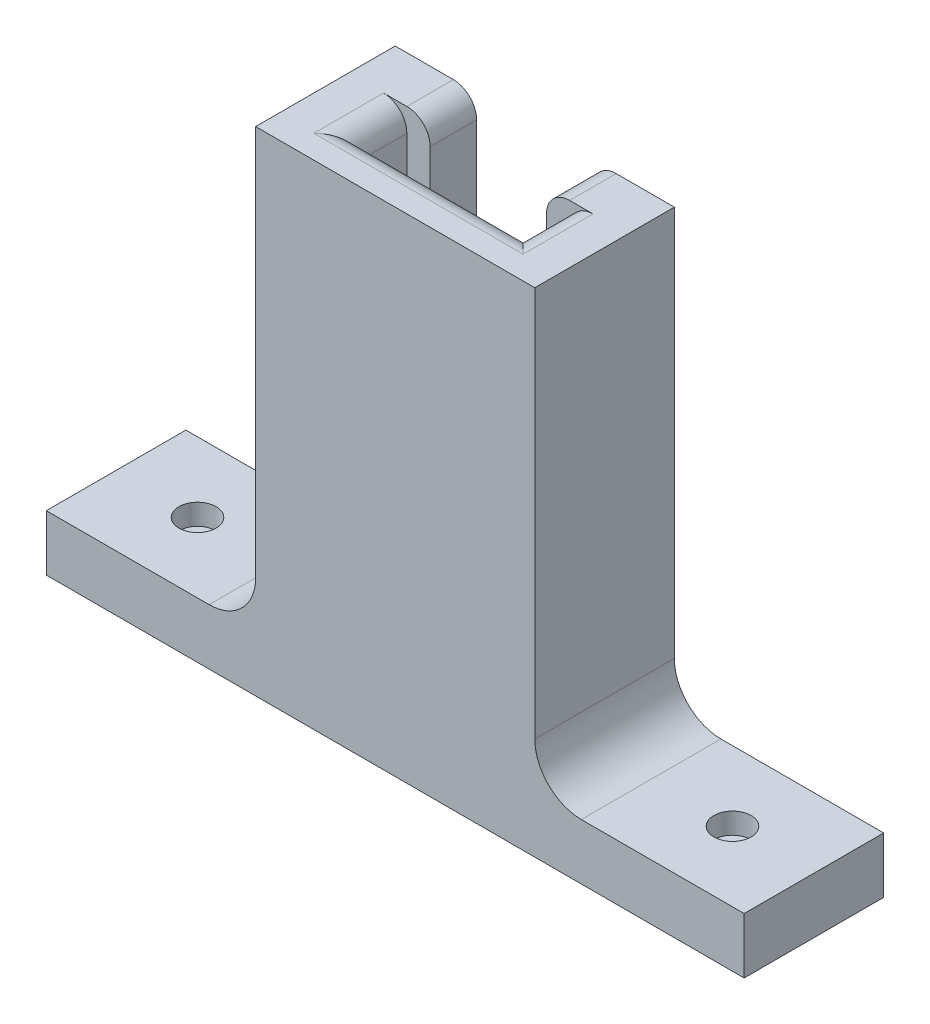
SolidWorks part; units mm, degrees
ref_plane "Front Plane" through (0, 0, 0) normal (0, 0, 1) x (1, 0, 0)
ref_plane "Top Plane" through (0, 0, 0) normal (0, 1, 0) x (1, 0, 0)
ref_plane "Right Plane" through (0, 0, 0) normal (1, 0, 0) x (0, 0, -1)
sketch "Sketch1" plane through (0, 0, 0) normal (0, 0, 1) x (1, 0, 0)
  line L1 (30, 50) -> (-30, 50)
  line L2 (30, 50) -> (30, -50)
  line L3 (30, -50) -> (-30, -50)
  line L4 (-30, 50) -> (-30, -50)
  line L5 (30, 50) -> (-30, -50) construction
  line L6 (30, -50) -> (-30, 50) construction
  line L7 (75, -44) -> (-75, -44)
  line L8 (75, -44) -> (75, -56)
  line L9 (75, -56) -> (-75, -56)
  line L10 (-75, -44) -> (-75, -56)
  line L11 (75, -44) -> (-75, -56) construction
  line L12 (75, -56) -> (-75, -44) construction
  point P0 (0, 0)
  point P6 (0, -50)
  dimension "D1" = 100
  dimension "D2" = 60
  dimension "D3" = 150
  dimension "D4" = 6
extrude "Boss-Extrude1" add sketch "Sketch1" along normal blind 30 contours L7 L10 L9 L8 L2 L3 L4
fillet "Fillet1" radius 10 2 edges at (30, -44, 15) (-30, -44, 15)
sketch "Sketch2" plane through (0, 50, 0) normal (0, 1, 0) x (1, 0, 0)
  line L1 (12.5, 15) -> (-12.5, 15)
  line L2 (12.5, 15) -> (12.5, -15)
  line L3 (12.5, -15) -> (-12.5, -15)
  line L4 (-12.5, 15) -> (-12.5, -15)
  line L5 (12.5, 15) -> (-12.5, -15) construction
  line L6 (12.5, -15) -> (-12.5, 15) construction
  line L7 (17.5, -10) -> (-17.5, -10)
  line L8 (17.5, -10) -> (17.5, -20)
  line L9 (17.5, -20) -> (-17.5, -20)
  line L10 (-17.5, -10) -> (-17.5, -20)
  line L11 (17.5, -10) -> (-17.5, -20) construction
  line L12 (17.5, -20) -> (-17.5, -10) construction
  point P0 (0, 0)
  point P6 (0, -15)
  line M5 (30, 0) -> (-30, 0)
  dimension "D1" = 25
  dimension "D2" = 30
  dimension "D3" = 10
  dimension "D4" = 35
extrude "Cut-Extrude1" cut sketch "Sketch2" against normal blind 222 contours L7 L2 L4 M5 | L2 L7 L4 L3 | L7 L10 L9 L8 L2 L3 L4
fillet "Fillet2" radius 5 5 edges at (12.5, 50, 5) (-12.5, 50, 5) (0, 50, 20) (-17.5, 50, 15) (17.5, 50, 15)
sketch "Sketch3" plane through (0, -44, 0) normal (0, 1, 0) x (1, 0, 0)
  line L0 (-40, 0) -> (-75, 0) construction
  line L1 (-75, -30) -> (-75, 0) construction
  circle A0 centre (-57.5, -15) radius 2
  point P4 (-57.5, 0)
  point P7 (-75, -15)
  dimension "D1" = 4
extrude "Cut-Extrude2" cut sketch "Sketch3" against normal blind 51
sketch "Sketch4" plane through (0, -44, 0) normal (0, 1, 0) x (1, 0, 0)
  circle A0 centre (-57.5, -15) radius 4
  dimension "D1" = 8
extrude "Cut-Extrude3" cut sketch "Sketch4" against normal blind 4.5
mirror "Mirror1" about plane through (0, 0, 0) normal (1, 0, 0) of "Cut-Extrude3", "Cut-Extrude2"
